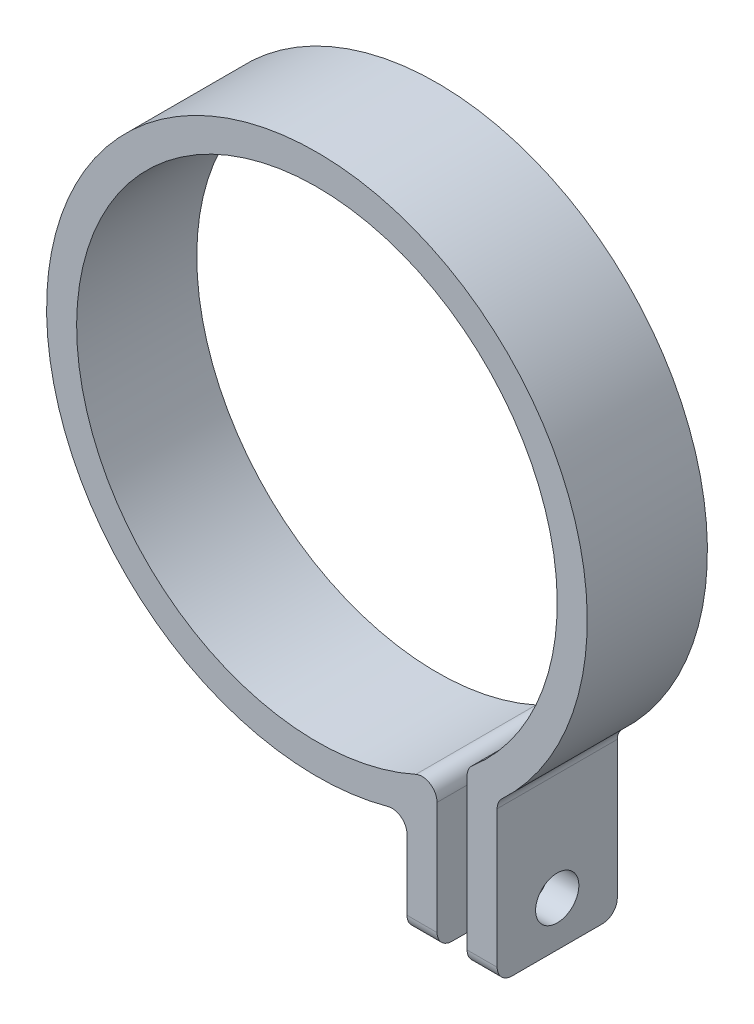
SolidWorks part; units mm, degrees
ref_plane "Front Plane" through (0, 0, 0) normal (0, 0, 1) x (1, 0, 0)
ref_plane "Top Plane" through (0, 0, 0) normal (0, 1, 0) x (1, 0, 0)
ref_plane "Right Plane" through (0, 0, 0) normal (1, 0, 0) x (0, 0, -1)
sketch "Sketch1" plane through (0, 0, 0) normal (0, 0, 1) x (1, 0, 0)
  line L0 (12.7, -21.997) -> (12.7, -38.1)
  line L1 (9.525, -26.9408) -> (9.525, -38.1)
  line L2 (9.525, -38.1) -> (12.7, -38.1)
  line L3 (15.875, -19.8279) -> (15.875, -38.1)
  line L4 (15.875, -38.1) -> (19.05, -38.1)
  line L5 (19.05, -38.1) -> (19.05, -21.2985)
  line L6 (-28.575, 0) -> (-28.575, -23.8501) construction
  arc A0 (15.875, -19.8279) -> (12.7, -21.997) centre (0, 0) ccw
  arc A1 (19.05, -21.2985) -> (9.525, -26.9408) centre (0, 0) ccw
  dimension "D1" = 50.8
  dimension "D2" = 3.175
  dimension "D3" = 3.175
  dimension "D4" = 3.175
  dimension "D5" = 3.175
  dimension "D6" = 38.1
  dimension "D7" = 41.275
extrude "Boss-Extrude1" add sketch "Sketch1" along normal mid plane 12.7
sketch "Sketch2" plane through (9.525, 0, 0) normal (-1, 0, 0) x (0, 0, 1)
  line L0 (6.35, -38.1) -> (-6.35, -38.1) construction
  circle A0 centre (0, -33.3375) radius 2.286
  point P4 (0, 0)
  dimension "D2" = 4.572
  dimension "D1" = 4.7625
extrude "Cut-Extrude1" cut sketch "Sketch2" against normal through all
fillet "Fillet1" radius 1.5875 8 edges at (9.525, -26.9408, 0) (19.05, -21.2985, 0) (12.7, -21.997, 0) (15.875, -19.8279, 0) (11.1125, -38.1, -6.35) (17.4625, -38.1, -6.35) (11.1125, -38.1, 6.35) (17.4625, -38.1, 6.35)
